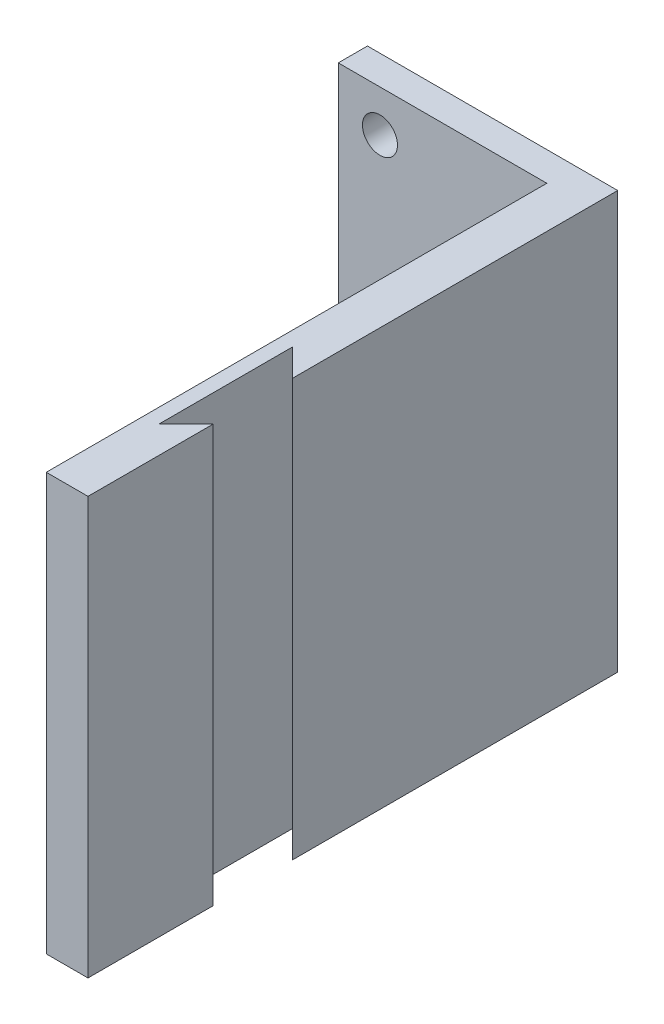
SolidWorks part; units mm, degrees
ref_plane "前视基准面" through (0, 0, 0) normal (0, 0, 1) x (1, 0, 0)
ref_plane "上视基准面" through (0, 0, 0) normal (0, 1, 0) x (1, 0, 0)
ref_plane "右视基准面" through (0, 0, 0) normal (1, 0, 0) x (0, 0, -1)
other "Configuration Table"
sketch "草图2" plane through (0, 0, 0) normal (0, 0, 1) x (1, 0, 0)
  line L0 (-15, 0) -> (15, 0) construction
  line L1 (-15, -25) -> (15, -25)
  line L2 (-15, -25) -> (-15, 25)
  line L3 (-15, 25) -> (15, 25)
  line L4 (15, -25) -> (15, 25)
  line L5 (-15, -25) -> (15, 25) construction
  line L6 (-15, 25) -> (15, -25) construction
  circle A0 centre (-10, -20) radius 2.1
  circle A1 centre (-10, 20) radius 2.1
  point P0 (0, 0)
  point P12 (0, 0)
  dimension "D3" = 40
  dimension "D1" = 30
  dimension "D2" = 50
extrude "凸台-拉伸1" add sketch "草图2" along normal blind 3.5
sketch "草图3" plane through (0, 0, 3.5) normal (0, 0, 1) x (1, 0, 0)
  line L0 (15, 25) -> (15, -25)
  line L1 (15, -25) -> (10, -25)
  line L2 (-15, -25) -> (15, -25) construction
  line L3 (10, -25) -> (10, 25)
  line L4 (10, 25) -> (15, 25)
  dimension "D1" = 5
extrude "凸台-拉伸2" add sketch "草图3" along normal blind 60
sketch "草图6" plane through (0, -25, 0) normal (0, -1, 0) x (1, 0, 0)
  line L0 (15, 48.5) -> (11.75, 51.75)
  line L1 (15, 63.5) -> (15, 0) construction
  line L2 (11.75, 51.75) -> (11.75, 35.75)
  line L3 (11.75, 35.75) -> (15, 39)
  line L4 (15, 39) -> (15, 48.5)
  dimension "D1" = 9.5
  dimension "D2" = 16
  dimension "D3" = 3.25
  dimension "D4" = 15
extrude "切除-拉伸1" cut sketch "草图6" against normal up to next
